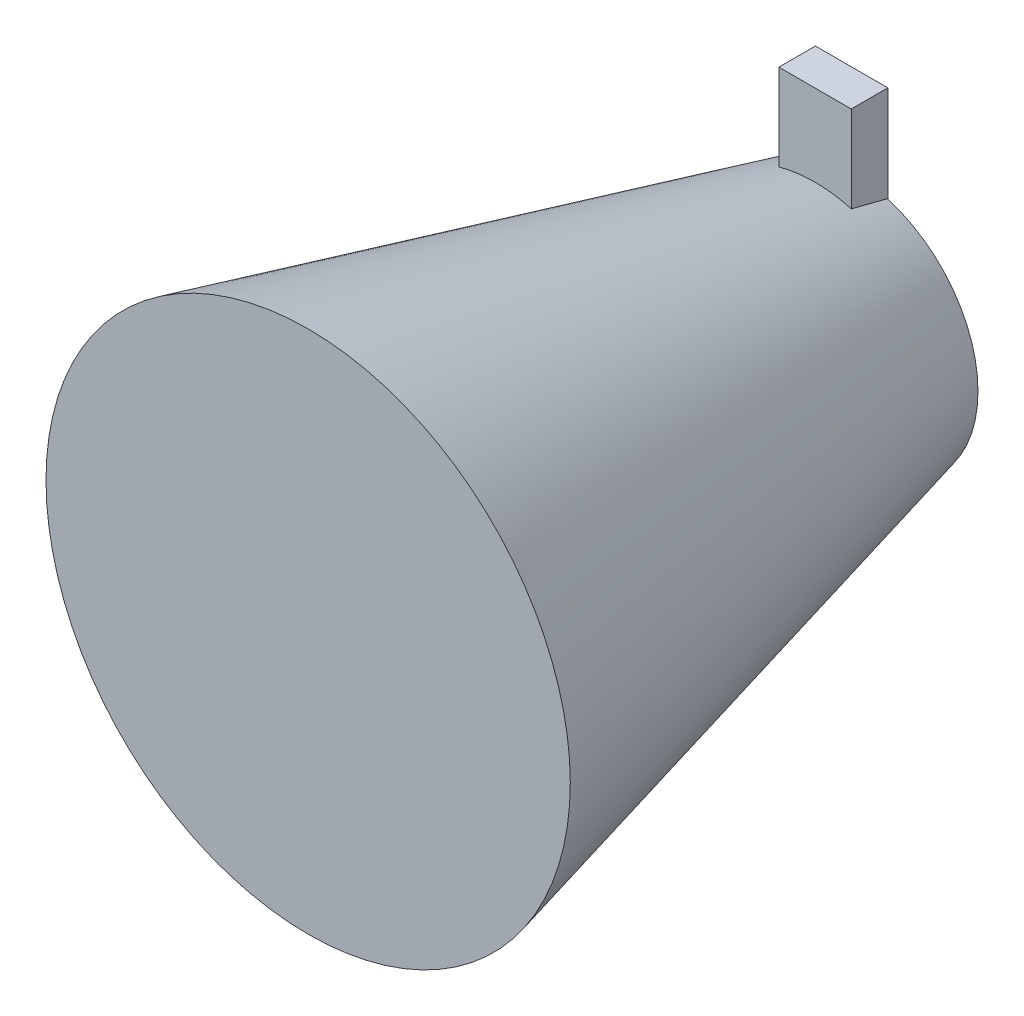
SolidWorks part; units mm, degrees
ref_plane "Plan de face" through (0, 0, 0) normal (0, 0, 1) x (1, 0, 0)
ref_plane "Plan de dessus" through (0, 0, 0) normal (0, 1, 0) x (1, 0, 0)
ref_plane "Plan de droite" through (0, 0, 0) normal (1, 0, 0) x (0, 0, -1)
sketch "Esquisse1" plane through (0, 0, 0) normal (0, 0, 1) x (1, 0, 0)
  circle A0 centre (-45.6455, 34.7889) radius 3.5
  dimension "D1" = 7
extrude "Boss.-Extru.1" add sketch "Esquisse1" along normal blind 15 draft 14 draft outward yes
sketch "Esquisse2" plane through (0, 0, 0) normal (0, 0, -1) x (-1, 0, 0)
  line L0 (49.1455, 34.7889) -> (42.1455, 34.7889) construction
  line L1 (45.6455, 38.2889) -> (45.6455, 31.2889) construction
  line L2 (46.7521, 44.793) -> (46.9926, 44.5429) construction
  line L4 (44.6455, 34.7889) -> (46.6455, 34.7889)
  line L5 (44.6455, 34.7889) -> (44.6455, 40.7889)
  line L6 (44.6455, 40.7889) -> (46.6455, 40.7889)
  line L7 (46.6455, 34.7889) -> (46.6455, 40.7889)
  circle A0 centre (45.6455, 34.7889) radius 3.5 construction
  dimension "D1" = 6
  dimension "D2" = 1
  dimension "D3" = 2
extrude "Boss.-Extru.2" add sketch "Esquisse2" along normal blind 0.01 and the other way blind 1 separate body
